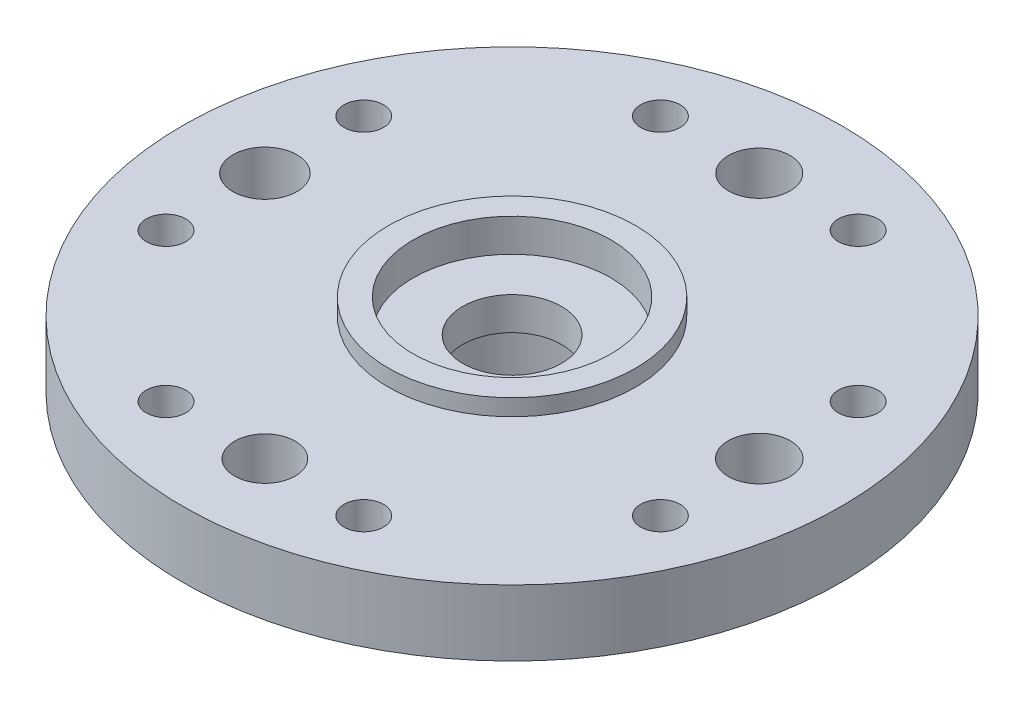
SolidWorks part; units mm, degrees
material "PVC rigide"
ref_plane "Plan de face" through (0, 0, 0) normal (0, 0, 1) x (1, 0, 0)
ref_plane "Plan de dessus" through (0, 0, 0) normal (0, 1, 0) x (1, 0, 0)
ref_plane "Plan de droite" through (0, 0, 0) normal (1, 0, 0) x (0, 0, -1)
sketch "Esquisse1" plane through (0, 0, 0) normal (0, 0, 1) x (1, 0, 0)
  line L0 (0, 0) -> (0, 5) construction
  line L1 (2.75, 0) -> (2.75, 3)
  line L2 (2.75, 3) -> (1.5, 3)
  line L3 (1.5, 3) -> (1.5, 4)
  line L4 (1.5, 4) -> (3, 4)
  line L5 (3, 4) -> (3, 5)
  line L6 (3, 5) -> (3.75, 5)
  line L7 (3.75, 5) -> (3.75, 4.5)
  line L8 (3.75, 4.5) -> (10, 4.5)
  line L9 (10, 4.5) -> (10, 2.5)
  line L10 (10, 2.5) -> (4.5, 2.5)
  line L11 (4.5, 2.5) -> (4.5, 0)
  line L12 (4.5, 0) -> (2.75, 0)
  dimension "D1" = 6
  dimension "D2" = 7.5
  dimension "D3" = 3
  dimension "D4" = 5.5
  dimension "D5" = 9
  dimension "D6" = 20
  dimension "D7" = 0.5
  dimension "D8" = 2
  dimension "D9" = 2.5
  dimension "D10" = 3
  dimension "D11" = 1
revolve "Révolution1" add sketch "Esquisse1" angle 360 about L0
sketch "Sketch1" plane through (0, 4.5, 0) normal (0, 1, 0) x (1, 0, 0)
  line L0 (0, 10) -> (0, -10) construction
  line L1 (-2.592, 7.5) -> (3, 7.5) construction
  circle A0 centre (0, 0) radius 10 construction
  circle A1 centre (0, 7.5) radius 0.6
  circle A2 centre (3, 7.5) radius 0.6
  circle A3 centre (-3, 7.5) radius 0.6
  dimension "D2" = 1.2
  dimension "D4" = 1.2
  dimension "D1" = 2.5
  dimension "D3" = 3
extrude "Cut-Extrude1" cut sketch "Sketch1" against normal up to surface (2 mm away) up to face at (0, 2.5, -10)
pattern_circular "CirPattern1" count 4 every 90 about axis through (0, 0, 0) along (0, 1, 0) of "Cut-Extrude1"
sketch "Esquisse2" plane through (0, 2.5, 0) normal (0, -1, 0) x (1, 0, 0)
  circle A0 centre (0, -7.5) radius 0.9345
  circle A1 centre (-7.5, 0) radius 0.971
  circle A2 centre (0, 7.5) radius 0.9197
  circle A3 centre (7.5, 0) radius 0.9409
extrude "Enlèv. mat.-Extru.1" cut sketch "Esquisse2" against normal through all
